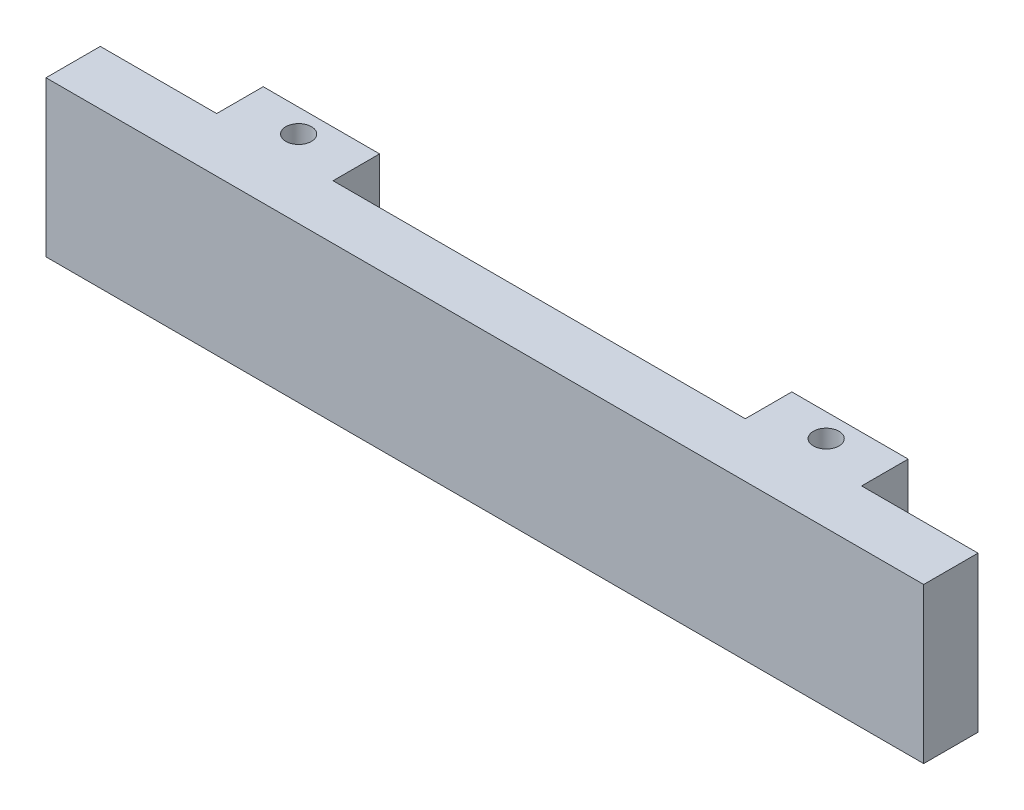
SolidWorks part; units mm, degrees
material "6061 合金"
ref_plane "前视基准面" through (0, 0, 0) normal (0, 0, 1) x (1, 0, 0)
ref_plane "上视基准面" through (0, 0, 0) normal (0, 1, 0) x (1, 0, 0)
ref_plane "右视基准面" through (0, 0, 0) normal (1, 0, 0) x (0, 0, -1)
sketch "草图1" plane through (0, 0, 0) normal (1, 0, 0) x (0, 0, -1)
  line L1 (-3.5, -10) -> (3.5, -10)
  line L2 (-3.5, -10) -> (-3.5, 10)
  line L3 (-3.5, 10) -> (3.5, 10)
  line L4 (3.5, -10) -> (3.5, 10)
  line L5 (-3.5, -10) -> (3.5, 10) construction
  line L6 (-3.5, 10) -> (3.5, -10) construction
  point P0 (0, 0)
  dimension "D1" = 7
  dimension "D2" = 20
extrude "凸台-拉伸1" add sketch "草图1" along normal mid plane 113.14
sketch "草图2" plane through (0, 0, -3.5) normal (0, 0, -1) x (-1, 0, 0)
  line L0 (-56.57, 10) -> (56.57, 10) construction
  line L1 (-26.57, -2) -> (-41.57, -2)
  line L2 (-26.57, -2) -> (-26.57, 10)
  line L3 (-26.57, 10) -> (-41.57, 10)
  line L4 (-41.57, -2) -> (-41.57, 10)
  line L5 (-26.57, -2) -> (-41.57, 10) construction
  line L6 (-26.57, 10) -> (-41.57, -2) construction
  line L7 (-56.57, -10) -> (56.57, -10) construction
  line L8 (-56.57, -10) -> (-56.57, 10) construction
  line L9 (0, 0) -> (0, 27.5606) construction
  point P0 (-34.07, 4)
  dimension "D1" = 8
  dimension "D2" = 15
  dimension "D3" = 15
extrude "凸台-拉伸2" add sketch "草图2" along normal blind 6
mirror "镜向1" about plane through (0, 0, 0) normal (1, 0, 0) of "凸台-拉伸2"
hole_wizard "M4 螺纹孔1" positions "草图4" profile "草图3" tap size "M4" standard "GB" end condition up to next
sketch "草图4" plane through (0, -2, 0) normal (0, -1, 0) x (-1, 0, 0)
  line L0 (0, 0) -> (0, 24.8691) construction
  line L1 (41.57, 9.5) -> (26.57, 9.5) construction
  point P6 (34, 6.5)
  point P8 (-34, 6.5)
  dimension "D1" = 3
  dimension "D2" = 68
sketch "草图3" plane through (-34, -2, -6.5) normal (1, 0, 0) x (0, 0, -1)
  line L0 (0, 0) -> (0, 12)
  line L1 (0, 12) -> (1.65, 12)
  line L2 (1.65, 12) -> (1.65, 0)
  line L5 (1.65, 0) -> (0, 0)
  line L11 (0, -6.35) -> (0, 107.95) construction
  dimension "通孔螺纹孔钻头直径" = 3.3
  dimension "通孔螺纹孔钻头深度" = 12
cosmetic thread "孔螺蚊线1" parameters "D2"=4
cosmetic thread "孔螺蚊线2" parameters "D2"=4
